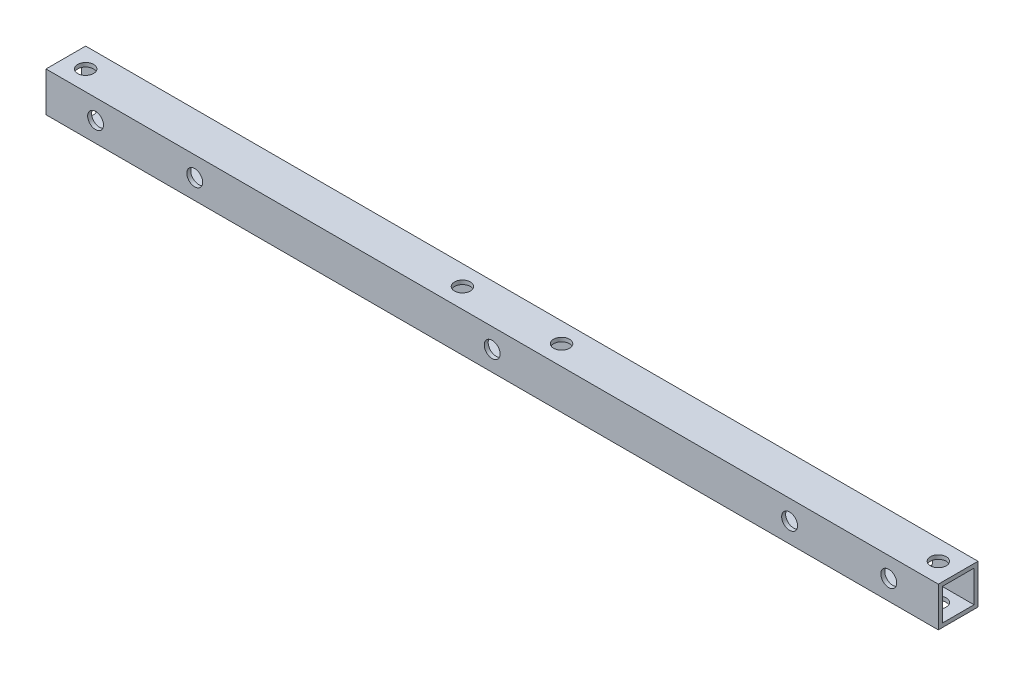
SolidWorks part; units mm, degrees
material "5052-H34"
ref_plane "正面" through (0, 0, 0) normal (0, 0, 1) x (1, 0, 0)
ref_plane "平面" through (0, 0, 0) normal (0, 1, 0) x (1, 0, 0)
ref_plane "右側面" through (0, 0, 0) normal (1, 0, 0) x (0, 0, -1)
sketch "ｽｹｯﾁ1" plane through (0, 0, 0) normal (1, 0, 0) x (0, 0, -1)
  line L1 (-5, 5) -> (5, 5)
  line L2 (-5, 5) -> (-5, -5)
  line L3 (-5, -5) -> (5, -5)
  line L4 (5, 5) -> (5, -5)
  line L5 (-5, 5) -> (5, -5) construction
  line L6 (-5, -5) -> (5, 5) construction
  point P0 (0, 0)
  dimension "D1" = 10
  dimension "D2" = 10
extrude "押し出し-薄板1" add sketch "ｽｹｯﾁ1" along normal blind 225 thin
sketch "ｽｹｯﾁ2" plane through (0, 0, 5) normal (0, 0, 1) x (1, 0, 0)
  line L0 (112.5, 5) -> (112.5, -5) construction
  line L1 (225, 5) -> (0, 5) construction
  line L2 (225, -5) -> (0, -5) construction
  line L3 (0, 0) -> (37.5, 0) construction
  line L4 (0, 5) -> (0, -5) construction
  circle A0 centre (37.5, 0) radius 2
  circle A1 centre (187.5, 0) radius 2
  circle A2 centre (112.5, 0) radius 2
  circle A3 centre (12.5, 0) radius 2
  circle A4 centre (212.5, 0) radius 2
  dimension "D1" = 4
  dimension "D3" = 4
  dimension "D4" = 25
  dimension "D2" = 37.5
extrude "ｶｯﾄ - 押し出し1" cut sketch "ｽｹｯﾁ2" against normal through all
sketch "ｽｹｯﾁ3" plane through (0, 5, 0) normal (0, 1, 0) x (1, 0, 0)
  line L0 (112.5, 5) -> (112.5, -5) construction
  line L1 (225, 5) -> (0, 5) construction
  line L2 (225, -5) -> (0, -5) construction
  line L3 (0, 0) -> (5, 0) construction
  line L4 (112.5, 0) -> (100, 0) construction
  line L5 (0, 5) -> (0, -5) construction
  line L6 (225, 5) -> (225, -5) construction
  circle A0 centre (5, 0) radius 2
  circle A1 centre (220, 0) radius 2
  circle A2 centre (100, 0) radius 2
  circle A3 centre (125, 0) radius 2
  dimension "D1" = 4
  dimension "D3" = 25
  dimension "D4" = 4
  dimension "D2" = 5
extrude "ｶｯﾄ - 押し出し2" cut sketch "ｽｹｯﾁ3" against normal through all
